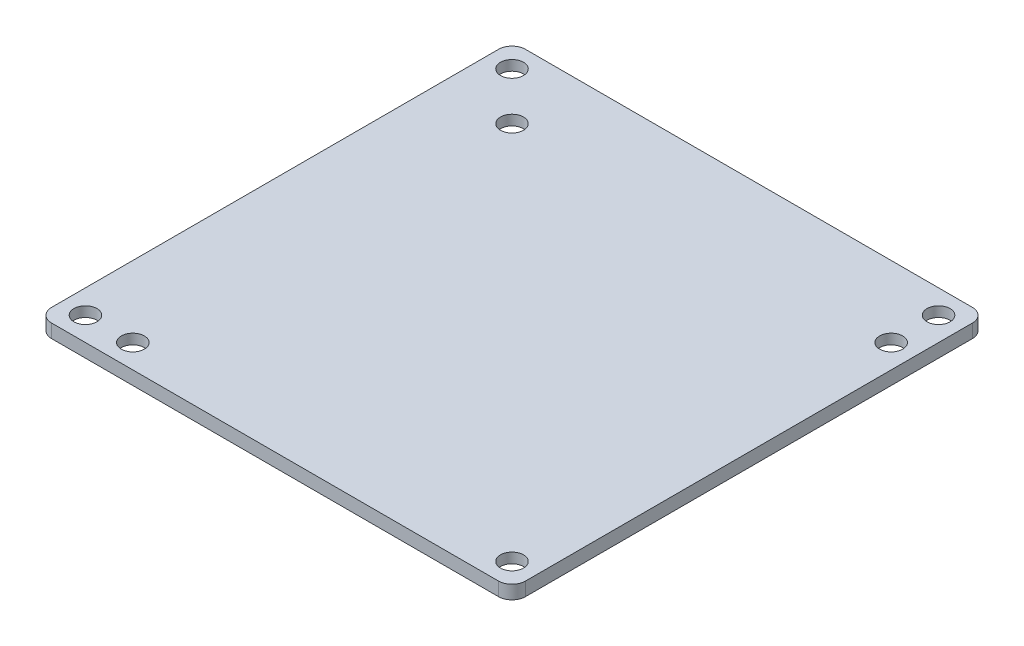
SolidWorks part; units mm, degrees
ref_plane "前视基准面" through (0, 0, 0) normal (0, 0, 1) x (1, 0, 0)
ref_plane "上视基准面" through (0, 0, 0) normal (0, 1, 0) x (1, 0, 0)
ref_plane "右视基准面" through (0, 0, 0) normal (1, 0, 0) x (0, 0, -1)
sketch "草图1" plane through (0, 0, 0) normal (0, 1, 0) x (1, 0, 0)
  line L0 (-65.779, 0) -> (65.779, 0) construction
  line L1 (0, -52.6408) -> (0, 52.6408) construction
  line L2 (-3.5, -52.6408) -> (-3.5, 52.6408) construction
  line L3 (-30, -30) -> (30, -30) construction
  line L4 (-30, -30) -> (-30, 30) construction
  line L5 (-30, 30) -> (30, 30) construction
  line L6 (30, -30) -> (30, 30) construction
  line L7 (-30, -30) -> (30, 30) construction
  line L8 (-30, 30) -> (30, -30) construction
  line L9 (-28, -28) -> (28, -28) construction
  line L10 (-28, -28) -> (-28, 28) construction
  line L11 (-28, 28) -> (28, 28) construction
  line L12 (28, -28) -> (28, 28) construction
  line L13 (-28, -28) -> (28, 28) construction
  line L14 (-28, 28) -> (28, -28) construction
  line L15 (-38.5, 38.5) -> (31.5, 38.5)
  line L16 (-38.5, 38.5) -> (-38.5, -31.5)
  line L17 (-38.5, -31.5) -> (31.5, -31.5)
  line L18 (31.5, 38.5) -> (31.5, -31.5)
  line L19 (-1, -22) -> (10, -22) construction
  line L20 (-1, -22) -> (-1, -31.5) construction
  line L21 (-1, -31.5) -> (10, -31.5) construction
  line L22 (10, -22) -> (10, -31.5) construction
  line L23 (27, 6) -> (31.5, 6) construction
  line L24 (27, 6) -> (27, -10) construction
  line L25 (27, -10) -> (31.5, -10) construction
  line L26 (31.5, 6) -> (31.5, -10) construction
  line L27 (27, -13) -> (31, -13) construction
  line L28 (27, -13) -> (27, -20.5) construction
  line L29 (27, -20.5) -> (31, -20.5) construction
  line L30 (31, -13) -> (31, -20.5) construction
  circle A0 centre (-28, -28) radius 1.7
  circle A1 centre (28, -28) radius 1.7
  circle A2 centre (28, 28) radius 1.7
  circle A3 centre (-28, 28) radius 1.7
  circle A4 centre (28, 35) radius 1.7
  circle A5 centre (-35, -28) radius 1.7
  circle A6 centre (-35, 35) radius 1.7
  point P0 (0, 0)
  point P3 (0, 0)
  point P4 (0, 0)
  point P8 (0, 0)
  point P40 (-3.5, 0)
  dimension "D3" = 3.4
  dimension "D1" = 60
  dimension "D2" = 56
  dimension "D4" = 29
  dimension "D5" = 40
  dimension "D6" = 8
  dimension "D7" = 20
  dimension "D8" = 36
  dimension "D9" = 3
  dimension "D10" = 1.5
  dimension "D11" = 1.5
  dimension "D12" = 9.5
  dimension "D13" = 17
  dimension "D14" = 1
  dimension "D15" = 3
  dimension "D16" = 70
  dimension "D17" = 3.5
  dimension "D18" = 3.5
extrude "凸台-拉伸1" add sketch "草图1" along normal blind 2
fillet "圆角1" radius 2 4 edges at (31.5, 1, 31.5) (-38.5, 1, 31.5) (-38.5, 1, -38.5) (31.5, 1, -38.5)
sketch "草图2" plane through (0, 0, 0) normal (0, -1, 0) x (1, 0, 0)
  line L0 (-61.5251, -3.5) -> (54.5251, -3.5) construction
  line L1 (-3.5, -44.6585) -> (-3.5, 37.6585) construction
  line L4 (31.5, -36.5) -> (31.5, 29.5)
  line L5 (29.5, 31.5) -> (-36.5, 31.5)
  line L6 (-38.5, 29.5) -> (-38.5, -36.5)
  line L7 (-36.5, -38.5) -> (29.5, -38.5)
  line L8 (31.5, -36.5) -> (31.5, 29.5)
  line L9 (29.5, 31.5) -> (-36.5, 31.5)
  line L10 (-38.5, 29.5) -> (-38.5, -36.5)
  line L11 (-36.5, -38.5) -> (29.5, -38.5)
  circle A0 centre (-35, 28) radius 1.7 construction
  circle A1 centre (-28, 28) radius 1.7 construction
  circle A2 centre (28, 28) radius 1.7 construction
  circle A3 centre (28, -28) radius 1.7 construction
  arc A4 (31.5, 29.5) -> (29.5, 31.5) centre (29.5, 29.5) ccw
  arc A5 (-36.5, 31.5) -> (-38.5, 29.5) centre (-36.5, 29.5) ccw
  arc A6 (-38.5, -36.5) -> (-36.5, -38.5) centre (-36.5, -36.5) ccw
  arc A7 (29.5, -38.5) -> (31.5, -36.5) centre (29.5, -36.5) ccw
  arc A8 (31.5, 29.5) -> (29.5, 31.5) centre (29.5, 29.5) ccw
  arc A9 (-36.5, 31.5) -> (-38.5, 29.5) centre (-36.5, 29.5) ccw
  arc A10 (-38.5, -36.5) -> (-36.5, -38.5) centre (-36.5, -36.5) ccw
  arc A11 (29.5, -38.5) -> (31.5, -36.5) centre (29.5, -36.5) ccw
  circle A12 centre (28, -35) radius 1.7 construction
  circle A13 centre (-28, -28) radius 1.7 construction
  circle A14 centre (-35, -35) radius 1.7 construction
  circle A15 centre (-35, -35) radius 1.7
  circle A16 centre (-28, -28) radius 1.7
  circle A17 centre (28, -35) radius 1.7
  circle A18 centre (28, -28) radius 1.7
  circle A19 centre (28, 28) radius 1.7
  circle A20 centre (-28, 28) radius 1.7
  circle A21 centre (-35, 28) radius 1.7
  circle A22 centre (-35, 28) radius 2.5
  circle A23 centre (-28, 28) radius 2.5
  circle A24 centre (28, 28) radius 2.5
  circle A25 centre (28, -28) radius 2.5
  circle A26 centre (28, -35) radius 2.5
  circle A27 centre (-28, -28) radius 2.5
  circle A28 centre (-35, -35) radius 2.5
  point P33 (-38.5, -3.5)
  point P34 (31.5, -3.5)
  point P35 (-3.5, 31.5)
  point P36 (-3.5, -38.5)
  point P40 (-3.5, -3.5)
  point P43 (-3.5, -3.5)
  circle M18 centre (-28, 28) radius 1.7
  circle M19 centre (28, 28) radius 1.7
  circle M20 centre (28, -28) radius 1.7
  circle M21 centre (-28, -28) radius 1.7
  circle M22 centre (28, -35) radius 1.7
  circle M23 centre (-35, 28) radius 1.7
  circle M24 centre (-35, -35) radius 1.7
  dimension "D1" = 0
  dimension "D2" = 0.8
extrude "切除-拉伸1" cut sketch "草图2" against normal blind 0.5 contours A23 M18 | A22 M23 | A24 M19 | A25 M20 | A26 M22 | A27 M21 | A28 M24
